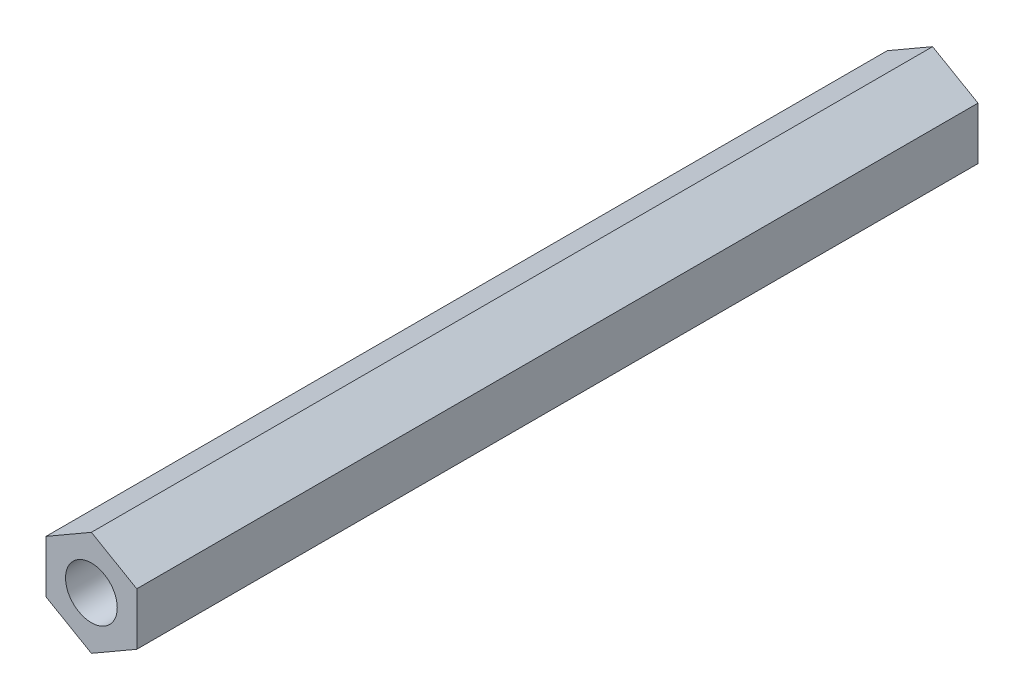
SolidWorks part; units mm, degrees
ref_plane "前视基准面" through (0, 0, 0) normal (0, 0, 1) x (1, 0, 0)
ref_plane "上视基准面" through (0, 0, 0) normal (0, 1, 0) x (1, 0, 0)
ref_plane "右视基准面" through (0, 0, 0) normal (1, 0, 0) x (0, 0, -1)
sketch "草图1" plane through (0, 0, 0) normal (0, 0, 1) x (1, 0, 0)
  line L0 (0, 0) -> (0, 4.05)
  line L1 (0, 4.05) -> (-3.5074, 2.025)
  line L2 (-3.5074, 2.025) -> (-3.5074, -2.025)
  line L3 (-3.5074, -2.025) -> (0, -4.05)
  line L4 (0, -4.05) -> (3.5074, -2.025)
  line L5 (3.5074, -2.025) -> (3.5074, 2.025)
  line L6 (3.5074, 2.025) -> (0, 4.05)
  circle A0 centre (0, 0) radius 3.5074 construction
  circle A1 centre (0, 0) radius 2
  dimension "D1" = 4
extrude "凸台-拉伸1" add sketch "草图1" along normal blind 65
